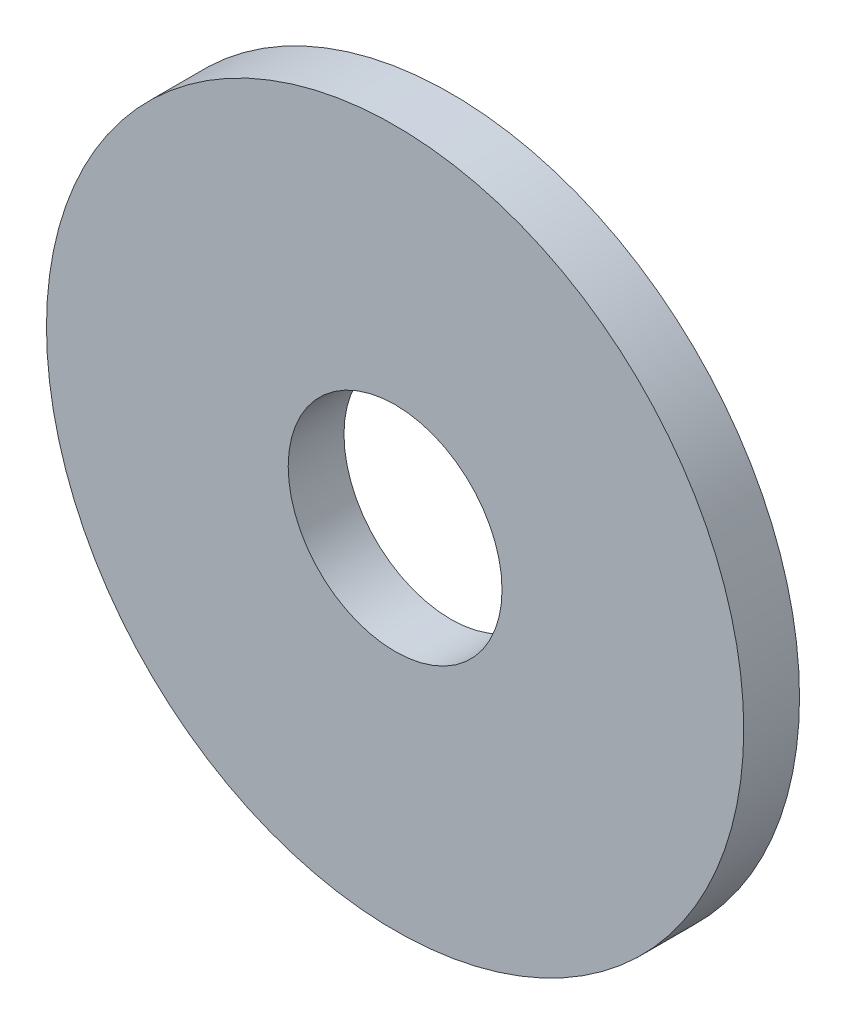
SolidWorks part; units mm, degrees
ref_plane "Alzado" through (0, 0, 0) normal (0, 0, 1) x (1, 0, 0)
ref_plane "Planta" through (0, 0, 0) normal (0, 1, 0) x (1, 0, 0)
ref_plane "Vista lateral" through (0, 0, 0) normal (1, 0, 0) x (0, 0, -1)
sketch "Croquis1" plane through (0, 0, 0) normal (0, 0, 1) x (1, 0, 0)
  circle A0 centre (0, 0) radius 7.5
  circle A1 centre (0, 0) radius 2.3
  dimension "D1" = 4.6
  dimension "D2" = 15
extrude "Saliente-Extruir1" add sketch "Croquis1" along normal blind 1.2
